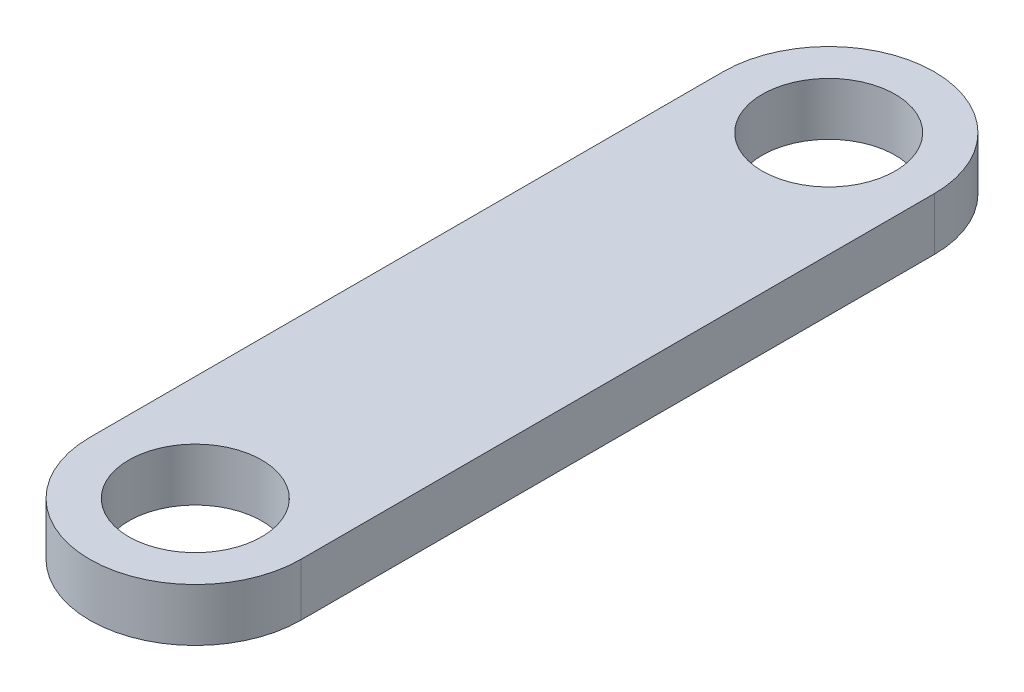
SolidWorks part; units mm, degrees
material "5052-H32"
ref_plane "X-Y Datum" through (0, 0, 0) normal (0, 0, 1) x (1, 0, 0)
ref_plane "X-Z Datum" through (0, 0, 0) normal (0, 1, 0) x (1, 0, 0)
ref_plane "Y-Z Datum" through (0, 0, 0) normal (1, 0, 0) x (0, 0, -1)
sketch "Sketch1" plane through (0, 0, 0) normal (0, 1, 0) x (1, 0, 0)
  line L0 (3.175, -19.05) -> (3.175, 0)
  line L1 (-3.175, -19.05) -> (-3.175, 0)
  circle A0 centre (0, 0) radius 2
  circle A1 centre (0, -19.05) radius 2
  arc A2 (3.175, -19.05) -> (-3.175, -19.05) centre (0, -19.05) cw
  arc A3 (3.175, 0) -> (-3.175, 0) centre (0, 0) ccw
  dimension "D1" = 4
  dimension "D3" = 19.05
  dimension "D4" = 6.35
extrude "Boss-Extrude1" add sketch "Sketch1" against normal blind 1.5875
